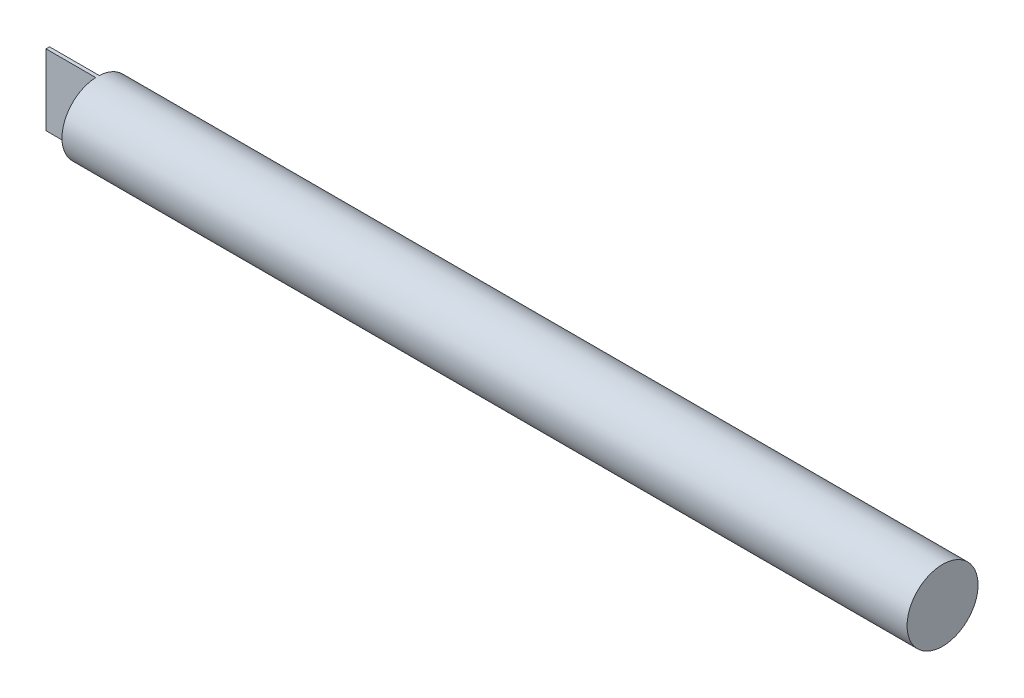
SolidWorks part; units mm, degrees
ref_plane "Front Plane" through (0, 0, 0) normal (0, 0, 1) x (1, 0, 0)
ref_plane "Top Plane" through (0, 0, 0) normal (0, 1, 0) x (1, 0, 0)
ref_plane "Right Plane" through (0, 0, 0) normal (1, 0, 0) x (0, 0, -1)
sketch "Sketch1" plane through (0, 0, 0) normal (0, 0, 1) x (1, 0, 0)
  line L0 (-63, 0) -> (63, 0) construction
  line L1 (-63, 0) -> (-63, 5)
  line L2 (-63, 5) -> (63, 5)
  line L3 (63, 5) -> (63, 0)
  line L4 (63, 0) -> (-63, 0)
  point P4 (0, 0)
  dimension "D1" = 126
  dimension "D2" = 10
revolve "Blank" add sketch "Sketch1" angle 360 about L0
sketch "Sketch2" plane through (-63, 0, 0) normal (-1, 0, 0) x (0, 0, 1)
  line L2 (-0.25, -4.9937) -> (-0.25, 4.9937)
  line L4 (0.25, -4.9937) -> (0.25, 4.9937)
  circle A0 centre (0, 0) radius 5
  point P4 (0, 0)
  circle M4 centre (0, 0) radius 5
  dimension "D1" = 10
  dimension "D2" = 0.5
extrude "Encaixe - Potenciômetro" cut sketch "Sketch2" against normal blind 7 contours L4 M4 | L2 M4
